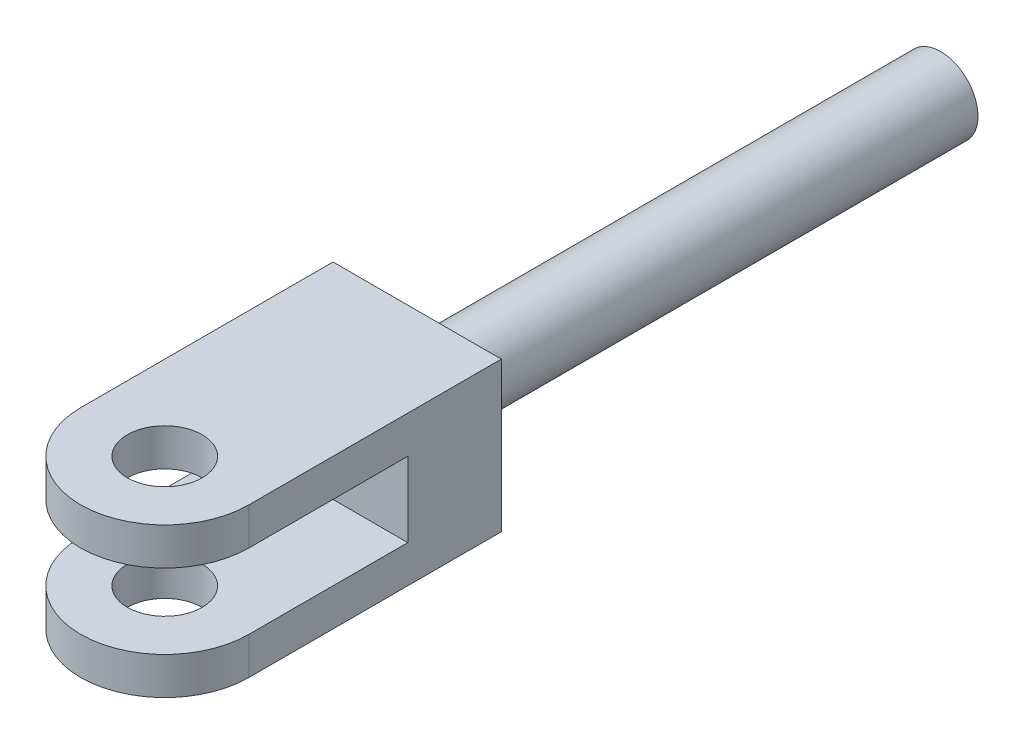
SolidWorks part; units mm, degrees
ref_plane "Front" through (0, 0, 0) normal (0, 0, 1) x (1, 0, 0)
ref_plane "Top" through (0, 0, 0) normal (0, 1, 0) x (1, 0, 0)
ref_plane "Right" through (0, 0, 0) normal (1, 0, 0) x (0, 0, -1)
sketch "Sketch1" plane through (0, 0, 0) normal (0, 0, 1) x (1, 0, 0)
  circle A0 centre (0, 0) radius 12.7
  dimension "D1" = 25.4
extrude "Extrude1" add sketch "Sketch1" along normal blind 177.8
sketch "Sketch2" plane through (0, 0, 0) normal (1, 0, 0) x (0, 0, -1)
  line L0 (-177.8, -25.4) -> (-177.8, 25.4)
  line L1 (-177.8, 25.4) -> (-292.1, 25.4)
  line L2 (-292.1, 25.4) -> (-292.1, 12.7)
  line L3 (-292.1, 12.7) -> (-209.55, 12.7)
  line L4 (-209.55, 12.7) -> (-209.55, -12.7)
  line L5 (-209.55, -12.7) -> (-292.1, -12.7)
  line L6 (-292.1, -12.7) -> (-292.1, -25.4)
  line L7 (-292.1, -25.4) -> (-177.8, -25.4)
  line L8 (-177.8, 0) -> (-270.3321, 0) construction
  line L9 (13.97, 0) -> (-13.97, 0) construction
  line L10 (-177.8, 12.7) -> (-177.8, -12.7) construction
  dimension "D1" = 25.4
  dimension "D2" = 12.7
  dimension "D3" = 82.55
  dimension "D4" = 31.75
extrude "Extrude2" add sketch "Sketch2" along normal mid plane 57.15
sketch "Sketch3" plane through (0, 25.4, 0) normal (0, 1, 0) x (-1, 0, 0)
  line L0 (0, 292.1) -> (0, 263.525) construction
  line L1 (-28.575, 292.1) -> (28.575, 292.1) construction
  line L2 (28.575, 177.8) -> (28.575, 292.1) construction
  line L3 (-28.575, 177.8) -> (-28.575, 292.1) construction
  line L4 (28.575, 263.525) -> (-28.575, 263.525) construction
  line L5 (28.575, 263.525) -> (28.575, 314.325)
  line L6 (28.575, 314.325) -> (-28.575, 314.325)
  line L7 (-28.575, 314.325) -> (-28.575, 263.525)
  circle A0 centre (0, 263.525) radius 12.7
  arc A1 (28.575, 263.525) -> (-28.575, 263.525) centre (0, 263.525) ccw
  dimension "D2" = 25.4
  dimension "D1" = 28.575
  dimension "D3" = 50.8
extrude "Cut-Extrude1" cut sketch "Sketch3" against normal through all
ref_plane "Plane1" through (0, 0, 263.525) normal (0, 0, 1) x (1, 0, 0)
ref_point "Point1"
